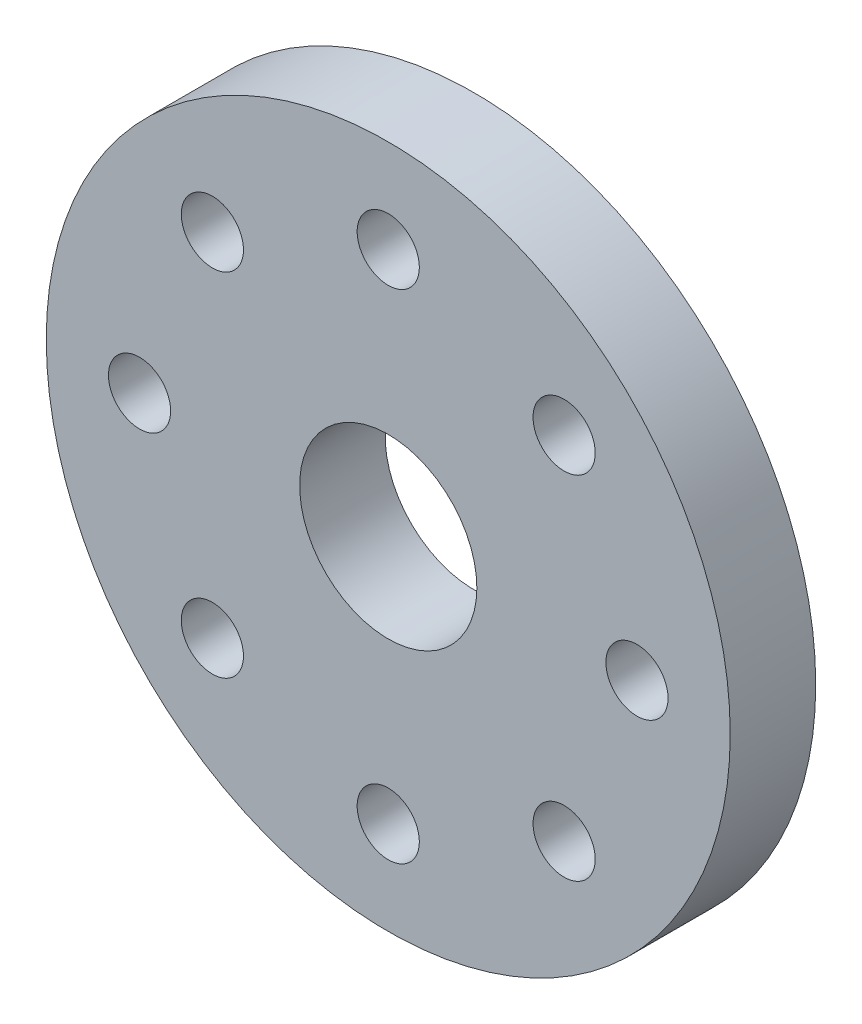
SolidWorks part; units mm, degrees
ref_plane "Front Plane" through (0, 0, 0) normal (0, 0, 1) x (1, 0, 0)
ref_plane "Top Plane" through (0, 0, 0) normal (0, 1, 0) x (1, 0, 0)
ref_plane "Right Plane" through (0, 0, 0) normal (1, 0, 0) x (0, 0, -1)
sketch "Sketch1" plane through (0, 0, 0) normal (0, 0, 1) x (1, 0, 0)
  circle A0 centre (0, 0) radius 11
  circle A1 centre (0, 0) radius 2.85
  dimension "D1" = 22
  dimension "D2" = 5.7
extrude "Boss-Extrude1" add sketch "Sketch1" along normal blind 2.75
sketch "Sketch2" plane through (0, 0, 2.75) normal (0, 0, 1) x (1, 0, 0)
  circle A0 centre (0, 0) radius 8 construction
  circle A1 centre (0, 8) radius 1
  circle A2 centre (5.6569, 5.6569) radius 1
  circle A3 centre (8, 0) radius 1
  circle A4 centre (5.6569, -5.6569) radius 1
  circle A5 centre (0, -8) radius 1
  circle A6 centre (-5.6569, -5.6569) radius 1
  circle A7 centre (-8, 0) radius 1
  circle A8 centre (-5.6569, 5.6569) radius 1
  point P21 (0, 0)
  dimension "D1" = 16
  dimension "D2" = 2
  dimension "D3" = 8
extrude "Cut-Extrude1" cut sketch "Sketch2" against normal through all
